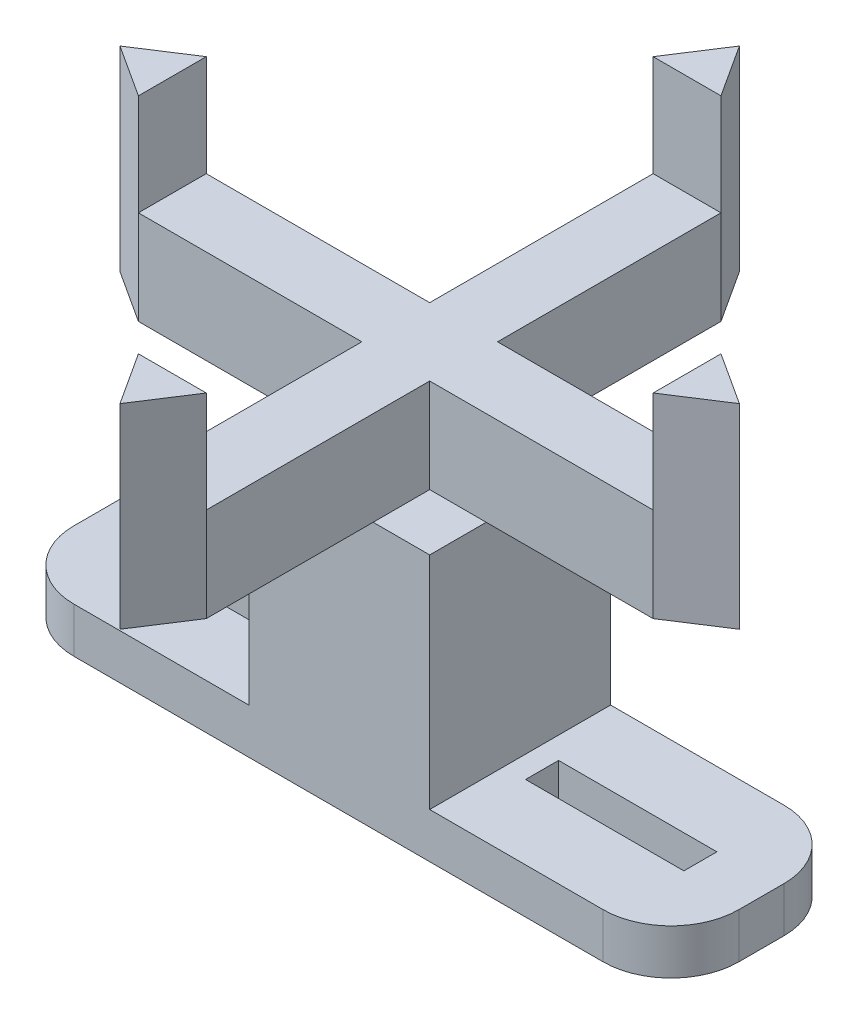
SolidWorks part; units mm, degrees
ref_plane "Front Plane" through (0, 0, 0) normal (0, 0, 1) x (1, 0, 0)
ref_plane "Top Plane" through (0, 0, 0) normal (0, 1, 0) x (1, 0, 0)
ref_plane "Right Plane" through (0, 0, 0) normal (1, 0, 0) x (0, 0, -1)
sketch "Sketch1" plane through (0, 0, 0) normal (0, 1, 0) x (1, 0, 0)
  line L0 (-68.059, -8.8969) -> (-61.059, -8.8969)
  line L7 (-67.759, -5.6269) -> (-44.359, -5.6269)
  line L10 (-70.759, -8.6269) -> (-70.759, -10.6269)
  line L11 (-67.759, -13.6269) -> (-44.359, -13.6269)
  line L12 (-41.359, -8.6269) -> (-41.359, -10.6269)
  line L17 (-51.059, -8.8969) -> (-44.059, -8.8969)
  line L18 (-51.059, -8.8969) -> (-51.059, -10.3569)
  line L19 (-51.059, -10.3569) -> (-44.059, -10.3569)
  line L20 (-44.059, -8.8969) -> (-44.059, -10.3569)
  line L21 (-68.059, -8.8969) -> (-68.059, -10.3569)
  line L22 (-68.059, -10.3569) -> (-61.059, -10.3569)
  line L23 (-61.059, -8.8969) -> (-61.059, -10.3569)
  arc A8 (-44.359, -5.6269) -> (-41.359, -8.6269) centre (-44.359, -8.6269) cw
  arc A9 (-44.359, -13.6269) -> (-41.359, -10.6269) centre (-44.359, -10.6269) ccw
  arc A10 (-70.759, -10.6269) -> (-67.759, -13.6269) centre (-67.759, -10.6269) ccw
  arc A11 (-67.759, -5.6269) -> (-70.759, -8.6269) centre (-67.759, -8.6269) ccw
  point P12 (-70.759, -9.6269)
  point P15 (-41.359, -5.6269)
  point P20 (-70.759, -13.6269)
  point P23 (-70.759, -5.6269)
  dimension "D1" = 2.7
  dimension "D2" = 8
  dimension "D3" = 29.4
  dimension "D9" = 3
  dimension "D4" = 7
  dimension "D5" = 1.46
  dimension "D6" = 2.7
  dimension "D7" = 3.27
  dimension "D8" = 3.27
extrude "Boss-Extrude2" add sketch "Sketch1" along normal blind 2
sketch "Sketch2" plane through (0, 2, 0) normal (0, 1, 0) x (1, 0, 0)
  line L21 (-44.359, -5.6269) -> (-67.759, -5.6269) construction
  line L22 (-60.0286, -5.6269) -> (-52.0286, -5.6269)
  line L23 (-60.0286, -5.6269) -> (-60.0286, -13.6269)
  line L24 (-60.0286, -13.6269) -> (-52.0286, -13.6269)
  line L25 (-52.0286, -5.6269) -> (-52.0286, -13.6269)
  line L26 (-67.759, -13.6269) -> (-44.359, -13.6269) construction
extrude "Boss-Extrude3" add sketch "Sketch2" along normal blind 9.7499
sketch "Sketch3" plane through (0, 11.7499, 0) normal (0, 1, 0) x (1, 0, 0)
  line L0 (-67.4086, -8.1269) -> (-57.5286, -8.1269)
  line L1 (-57.5286, -8.1269) -> (-57.5286, 1.7531)
  line L2 (-57.5286, 1.7531) -> (-54.5286, 1.7531)
  line L3 (-54.5286, 1.7531) -> (-54.5286, -8.1269)
  line L4 (-54.5286, -8.1269) -> (-44.6486, -8.1269)
  line L5 (-44.6486, -8.1269) -> (-44.6486, -11.1269)
  line L6 (-44.6486, -11.1269) -> (-54.5286, -11.1269)
  line L7 (-54.5286, -11.1269) -> (-54.5286, -21.0069)
  line L8 (-54.5286, -21.0069) -> (-57.5286, -21.0069)
  line L9 (-57.5286, -21.0069) -> (-57.5286, -11.1269)
  line L10 (-57.5286, -11.1269) -> (-67.4086, -11.1269)
  line L11 (-67.4086, -11.1269) -> (-67.4086, -8.1269)
  line L12 (-52.0286, -5.6269) -> (-60.0286, -5.6269) construction
  line L13 (-60.0286, -5.6269) -> (-60.0286, -13.6269) construction
  dimension "D1" = 3
  dimension "D2" = 9.88
  dimension "D3" = 2.5
  dimension "D4" = 2.5
extrude "Boss-Extrude4" add sketch "Sketch3" along normal blind 4.16
sketch "Sketch4" plane through (0, 11.7499, 0) normal (0, 1, 0) x (1, 0, 0)
  line L0 (-67.4086, -8.1269) -> (-69.7238, -9.6269)
  line L1 (-69.7238, -9.6269) -> (-67.4086, -11.1269)
  line L2 (-67.4086, -8.1269) -> (-67.4086, -11.1269) construction
  line L3 (-67.4086, -11.1269) -> (-67.4086, -8.1269)
  point P6 (-67.4086, -11.1269)
  dimension "D1" = 2.3153
extrude "Boss-Extrude5" add sketch "Sketch4" along normal blind 8.6408
sketch "Sketch6" plane through (0, 0, 0) normal (0, 1, 0) x (1, 0, 0)
  line L0 (-44.6486, -8.1269) -> (-54.5286, -8.1269) construction
  line L1 (-54.5286, -13.6269) -> (-54.5286, -11.1269) construction
  circle A0 centre (-56.0286, -9.6269) radius 1.5
  dimension "D1" = 3
  dimension "D2" = 1.5
  dimension "D3" = 1.5
extrude "Boss-Extrude7" add sketch "Sketch6" along normal blind 0.5
pattern_circular "CirPattern2" count 4 over 360 about axis through (-56.0286, 0, 9.6269) along (0, 1, 0) of "Boss-Extrude5"
